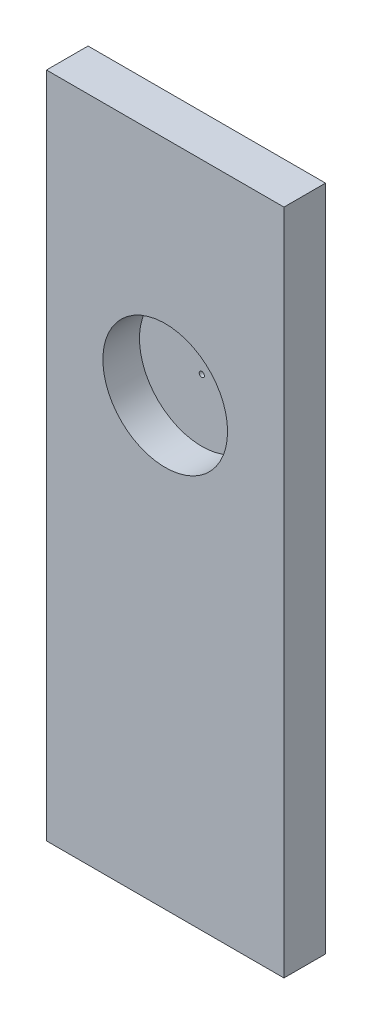
SolidWorks part; units mm, degrees
material "Brass"
ref_plane "Front Plane" through (0, 0, 0) normal (0, 0, 1) x (1, 0, 0)
ref_plane "Top Plane" through (0, 0, 0) normal (0, 1, 0) x (1, 0, 0)
ref_plane "Right Plane" through (0, 0, 0) normal (1, 0, 0) x (0, 0, -1)
sketch "Sketch1" plane through (0, 0, 0) normal (0, 0, 1) x (1, 0, 0)
  line L0 (-18.1394, 51.0016) -> (18.1394, -51.0016) construction
  line L1 (-18.1394, 51.0016) -> (18.1394, 51.0016)
  line L2 (-18.1394, 51.0016) -> (-18.1394, -51.0016)
  line L3 (-18.1394, -51.0016) -> (18.1394, -51.0016)
  line L4 (18.1394, 51.0016) -> (18.1394, -51.0016)
  line L5 (0, -1000) -> (0, 49000) construction
  dimension "D1" = 36.2788
  dimension "D2" = 102.0032
extrude "Extrude1" add sketch "Sketch1" along normal blind 6.35
sketch "Sketch2" plane through (0, 0, 6.35) normal (0, 0, 1) x (1, 0, 0)
  line L0 (0, -1000) -> (0, 49000) construction
  line L2 (-18.1394, -51.0016) -> (18.1394, -51.0016) construction
  circle A0 centre (0, 17.0005) radius 9.525
  dimension "D2" = 19.05
  dimension "D1" = 68.0022
extrude "Extrude2" cut sketch "Sketch2" against normal blind 5.588
sketch "Sketch3" plane through (0, 0, 0.762) normal (0, 0, 1) x (1, 0, 0)
  line L0 (0, -1000) -> (0, 49000) construction
  line L2 (-18.1394, -51.0016) -> (18.1394, -51.0016) construction
  circle A0 centre (0, 17.0005) radius 0.3969
  dimension "D2" = 0.7937
  dimension "D1" = 68.0022
extrude "Extrude3" cut sketch "Sketch3" against normal through all
hole_wizard "#3-48 Tapped Hole1" positions "Sketch4" profile "Sketch5" tap size "#3-48" standard "Ansi Inch"
sketch "Sketch4" plane through (-14.071, -51.0016, -59.6487) normal (0, -1, 0) x (0, 0, -1)
  point P0 (-62.8237, 25.8604)
  point P1 (-62.8237, 0.8922)
sketch "Sketch5" plane through (11.7894, -51.0016, 3.175) normal (1, 0, 0) x (0, 0, -1)
  line L0 (0, 0) -> (0, 9.743)
  line L1 (0, 9.743) -> (0.9969, 9.144)
  line L2 (0.9969, 9.144) -> (0.997, 7.62)
  line L3 (0.997, 7.62) -> (1.2573, 7.62)
  line L4 (1.2573, 7.62) -> (1.2573, 0)
  line L5 (1.2573, 0) -> (0, 0)
  line L10 (0, 9.743) -> (-0.997, 9.144) construction
  line L11 (0, -6.35) -> (0, 107.95) construction
  dimension "Tap Drill Dia." = 1.9939
  dimension "Tap Drill Depth" = 9.144
  dimension "Thread Major Dia." = 2.5146
  dimension "Drill Angle" = 118
  dimension "Thread Depth Difference" = 1.524
